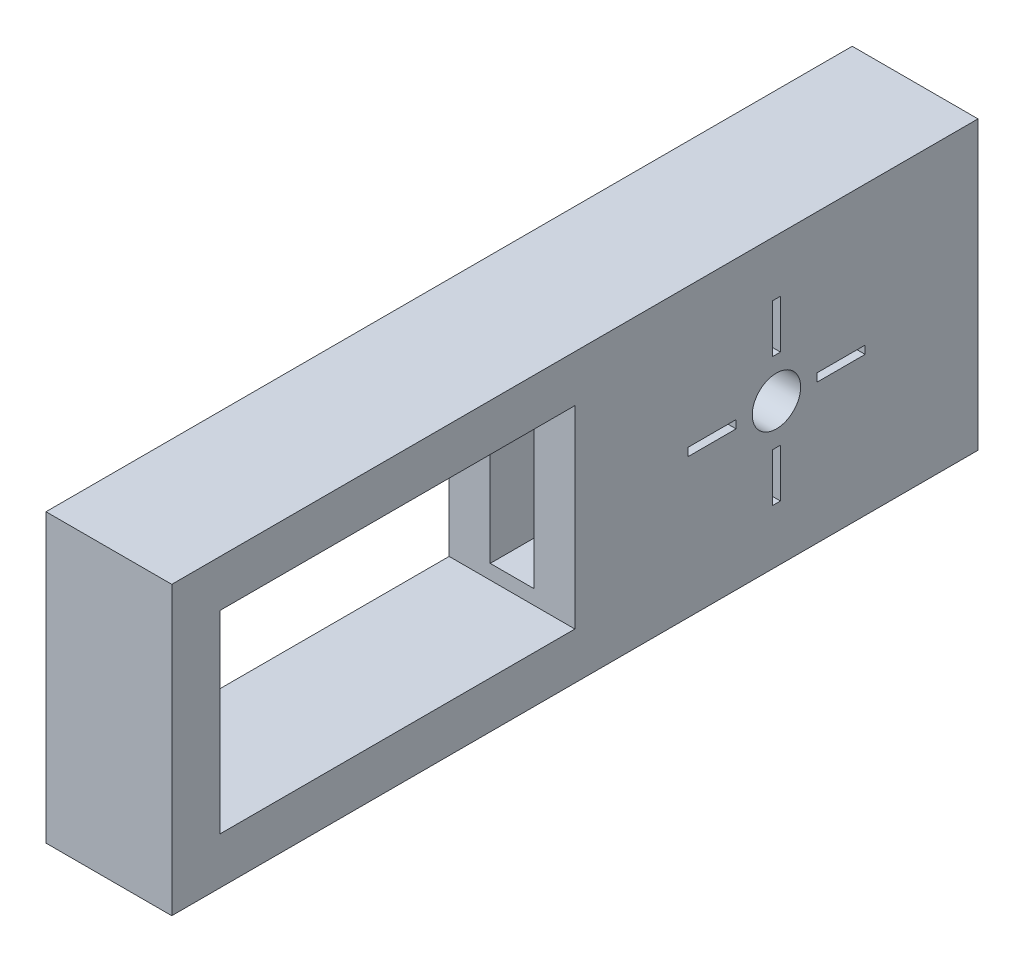
SolidWorks part; units mm, degrees
ref_plane "Front Plane" through (0, 0, 0) normal (1, 0, 0) x (0, 1, 0)
ref_plane "Top Plane" through (0, 0, 0) normal (0, 0, 1) x (0, 1, 0)
ref_plane "Right Plane" through (0, 0, 0) normal (0, 1, 0) x (-1, 0, 0)
sketch "Sketch1" plane through (0, 0, 0) normal (1, 0, 0) x (0, 1, 0)
  line L1 (8.9, -12.5) -> (-8.9, -12.5)
  line L2 (8.9, -12.5) -> (8.9, 12.5)
  line L3 (8.9, 12.5) -> (-8.9, 12.5)
  line L4 (-8.9, -12.5) -> (-8.9, 12.5)
  line L5 (8.9, -12.5) -> (-8.9, 12.5) construction
  line L6 (8.9, 12.5) -> (-8.9, -12.5) construction
  circle A0 centre (0, 0) radius 1.5
  point P0 (0, 0)
  dimension "D3" = 3
  dimension "D1" = 17.8
  dimension "D2" = 25
extrude "Boss-Extrude1" add sketch "Sketch1" along normal mid plane 7.8
ref_plane "Plane2" through (3.9, 0, 0) normal (1, 0, 0) x (0, 0, -1)
sketch "Sketch3" plane through (3.9, 0, 0) normal (1, 0, 0) x (0, 0, -1)
  line L0 (0, 6.4027) -> (0, -6.2592) construction
  line L1 (-6.3453, 0) -> (7.465, 0) construction
  line L3 (-0.25, 5.5) -> (0.25, 5.5)
  line L4 (-0.25, 5.5) -> (-0.25, 2.5)
  line L5 (-0.25, 2.5) -> (0.25, 2.5)
  line L6 (0.25, 5.5) -> (0.25, 2.5)
  line L7 (-0.25, 5.5) -> (0.25, 2.5) construction
  line L8 (-0.25, 2.5) -> (0.25, 5.5) construction
  point P5 (0, 4)
  dimension "D1" = 0.5
  dimension "D2" = 3
  dimension "D3" = 4
extrude "Cut-Extrude1" cut sketch "Sketch3" against normal blind 10
pattern_circular "CirPattern1" count 4 over 360 about axis through (0, 0, 0) along (1, 0, 0) of "Cut-Extrude1"
ref_plane "Plane3" through (0, 0, 12.5) normal (0, 0, 1) x (1, 0, 0)
sketch "Sketch4" plane through (0, 0, 12.5) normal (0, 0, 1) x (1, 0, 0)
  line L1 (1.35, -5.1) -> (-1.35, -5.1)
  line L2 (1.35, -5.1) -> (1.35, 5.1)
  line L3 (1.35, 5.1) -> (-1.35, 5.1)
  line L4 (-1.35, -5.1) -> (-1.35, 5.1)
  line L5 (1.35, -5.1) -> (-1.35, 5.1) construction
  line L6 (1.35, 5.1) -> (-1.35, -5.1) construction
  point P0 (0, 0)
  dimension "D1" = 2.7
  dimension "D2" = 10.2
extrude "Cut-Extrude2" cut sketch "Sketch4" against normal blind 18
ref_plane "Plane4" through (0, 0, -12.5) normal (0, 0, -1) x (-1, 0, 0)
sketch "Sketch5" plane through (0, 0, -12.5) normal (0, 0, -1) x (-1, 0, 0)
  line L1 (1.4, -4.5) -> (-1.4, -4.5)
  line L2 (1.4, -4.5) -> (1.4, 4.5)
  line L3 (1.4, 4.5) -> (-1.4, 4.5)
  line L4 (-1.4, -4.5) -> (-1.4, 4.5)
  line L5 (1.4, -4.5) -> (-1.4, 4.5) construction
  line L6 (1.4, 4.5) -> (-1.4, -4.5) construction
  point P0 (0, 0)
  dimension "D1" = 2.8
  dimension "D2" = 9
extrude "Cut-Extrude3" cut sketch "Sketch5" against normal blind 10
sketch "Sketch6" plane through (0, 0, 12.5) normal (0, 0, 1) x (1, 0, 0)
  line L0 (3.9, -9.79) -> (3.9, 9.79) construction
  line L1 (-3.9, 8.9) -> (3.9, 8.9)
  line L2 (-3.9, 8.9) -> (-3.9, -8.9)
  line L3 (-3.9, -8.9) -> (3.9, -8.9)
  line L4 (3.9, 8.9) -> (3.9, -8.9)
  dimension "D1" = 17.8
extrude "Boss-Extrude2" add sketch "Sketch6" along normal blind 25
sketch "Sketch7" plane through (3.9, 0, 0) normal (1, 0, 0) x (0, 0, -1)
  line L0 (0, 0) -> (-34.4467, 0) construction
  line L2 (-12.5, -6) -> (-34.5, -6)
  line L3 (-12.5, -6) -> (-12.5, 6)
  line L4 (-12.5, 6) -> (-34.5, 6)
  line L5 (-34.5, -6) -> (-34.5, 6)
  line L6 (-12.5, -6) -> (-34.5, 6) construction
  line L7 (-12.5, 6) -> (-34.5, -6) construction
  point P3 (-23.5, 0)
  dimension "D1" = 22
  dimension "D2" = 12
  dimension "D3" = 12.5
extrude "Cut-Extrude4" cut sketch "Sketch7" against normal blind 30
